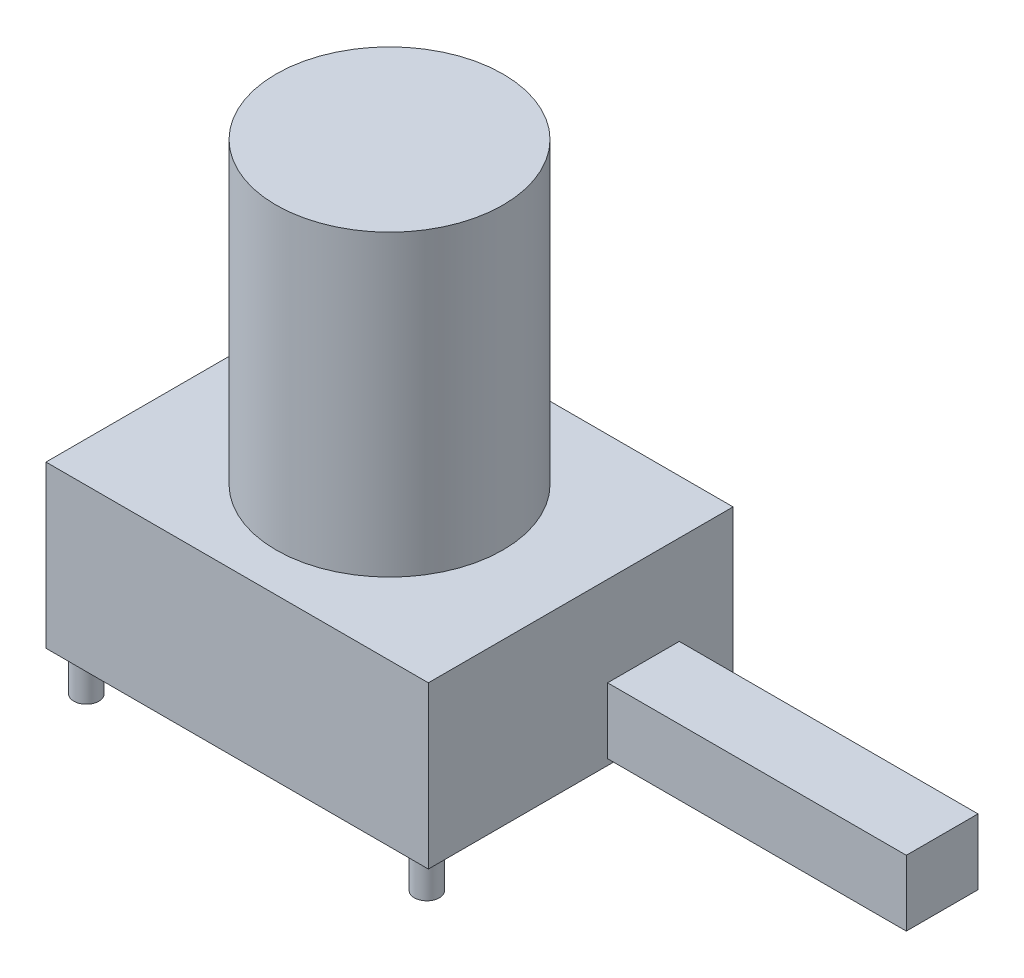
SolidWorks part; units mm, degrees
ref_plane "Front Plane" through (0, 0, 0) normal (0, 0, 1) x (1, 0, 0)
ref_plane "Top Plane" through (0, 0, 0) normal (0, 1, 0) x (1, 0, 0)
ref_plane "Right Plane" through (0, 0, 0) normal (1, 0, 0) x (0, 0, -1)
sketch "Sketch1" plane through (0, 0, 0) normal (0, 1, 0) x (1, 0, 0)
  line L1 (0, 0) -> (64, 0)
  line L2 (0, 0) -> (0, 51)
  line L3 (0, 51) -> (64, 51)
  line L4 (64, 0) -> (64, 51)
  dimension "D1" = 64
  dimension "D2" = 51
extrude "Boss-Extrude1" add sketch "Sketch1" along normal blind 27
sketch "Sketch2" plane through (0, 27, 0) normal (0, 1, 0) x (1, 0, 0)
  line L0 (0, 0) -> (64, 51) construction
  line L3 (64, 0) -> (0, 51) construction
  circle A0 centre (32, 25.5) radius 19
extrude "Boss-Extrude2" add sketch "Sketch2" along normal blind 50
sketch "Sketch3" plane through (0, 0, 0) normal (0, -1, 0) x (1, 0, 0)
  line L0 (32, 0) -> (32, -51) construction
  line L1 (0, 0) -> (64, 0) construction
  line L2 (64, -51) -> (0, -51) construction
  line L3 (0, -25.5) -> (64, -25.5) construction
  line L4 (0, -51) -> (0, 0) construction
  line L5 (64, 0) -> (64, -51) construction
  circle A0 centre (3.5, -3.25) radius 2.1
  circle A1 centre (60.5, -3.25) radius 2.1
  circle A2 centre (3.5, -47.75) radius 2.1
  circle A3 centre (60.5, -47.75) radius 2.1
  dimension "D2" = 4.2
  dimension "D3" = 4.2
  dimension "D4" = 4.2
  dimension "D5" = 4.2
  dimension "D1" = 57
  dimension "D6" = 44.5
  dimension "D7" = 28.5
  dimension "D8" = 22.25
extrude "Boss-Extrude3" add sketch "Sketch3" along normal blind 6.5
sketch "Sketch4" plane through (64, 0, 0) normal (1, 0, 0) x (0, 0, -1)
  line L0 (51, 27) -> (51, 0) construction
  line L1 (42, 1) -> (30, 1)
  line L2 (42, 1) -> (42, 12)
  line L3 (42, 12) -> (30, 12)
  line L4 (30, 1) -> (30, 12)
  line L5 (0, 0) -> (51, 0) construction
  dimension "D1" = 12
  dimension "D2" = 11
  dimension "D3" = 9
  dimension "D4" = 1
extrude "Boss-Extrude4" add sketch "Sketch4" along normal blind 50
equation "\"D3@Sketch3\"=\"D2@Sketch3\""
equation "\"D4@Sketch3\"=\"D2@Sketch3\""
equation "\"D5@Sketch3\"=\"D2@Sketch3\""
equation "\"D7@Sketch3\"=\"D1@Sketch3\"/2"
equation "\"D8@Sketch3\"=\"D6@Sketch3\"/2"
